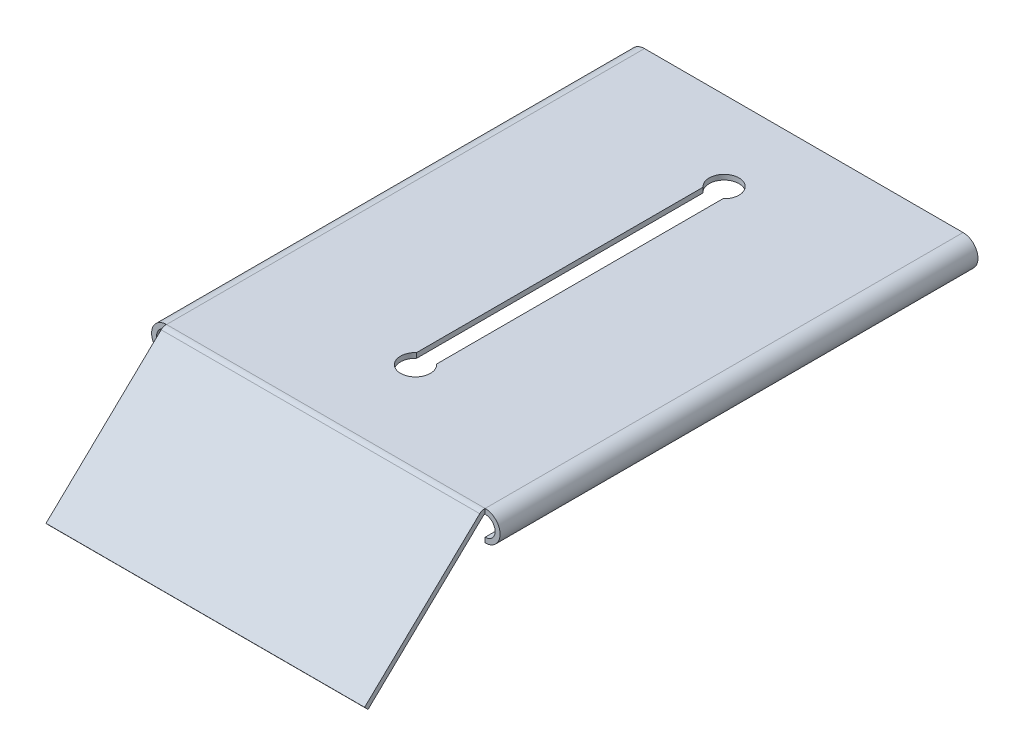
SolidWorks part; units mm, degrees
ref_plane "Front Plane" through (0, 0, 0) normal (0, 0, 1) x (1, 0, 0)
ref_plane "Top Plane" through (0, 0, 0) normal (0, 1, 0) x (1, 0, 0)
ref_plane "Right Plane" through (0, 0, 0) normal (1, 0, 0) x (0, 0, -1)
sketch "Sketch1" plane through (0, 0, 0) normal (0, 0, 1) x (1, 0, 0)
  line L0 (0, 0) -> (-101.6, 0)
  arc A0 (0, 0) -> (0, -6.35) centre (0, -3.175) cw
  arc A1 (-101.6, 0) -> (-101.6, -6.35) centre (-101.6, -3.175) ccw
  dimension "D1" = 6.35
  dimension "D2" = 101.6
extrude "Extrude-Thin1" add sketch "Sketch1" along normal blind 152.4 thin
sketch "Sketch3" plane through (0, 1.5875, 0) normal (0, 1, 0) x (1, 0, 0)
  line L0 (-50.8, 0) -> (-50.8, -152.4) construction
  line L1 (0, 0) -> (-101.6, 0) construction
  line L2 (0, -152.4) -> (-101.6, -152.4) construction
  line L3 (-53.975, -120.2752) -> (-53.975, -28.9498)
  line L4 (-50.8, -25.4) -> (-50.8, -123.825) construction
  line L6 (-47.625, -120.2752) -> (-47.625, -28.9498)
  line L7 (-53.975, -120.2752) -> (-47.625, -28.9498) construction
  line L8 (-53.975, -28.9498) -> (-47.625, -120.2752) construction
  arc A0 (-53.975, -28.9498) -> (-47.625, -28.9498) centre (-50.8, -25.4) cw
  arc A1 (-47.625, -120.2752) -> (-53.975, -120.2752) centre (-50.8, -123.825) cw
  point P7 (-50.8, -74.6125)
  dimension "D2" = 4.7625
  dimension "D3" = 123.825
  dimension "D1" = 6.35
  dimension "D4" = 25.4
extrude "Cut-Extrude1" cut sketch "Sketch3" against normal through all
sketch "Sketch4" plane through (0, 0, 0) normal (1, 0, 0) x (0, 0, -1)
  line L0 (-154.1261, 0.9974) -> (-190.8442, -34.1084)
  line L1 (-190.8442, -34.1084) -> (-189.7472, -35.2558)
  line L2 (-189.7472, -35.2558) -> (-153.029, -0.15)
  line L3 (-152.4, 0) -> (-152.4, 1.5875)
  line L4 (-154.1261, 0.9974) -> (-153.029, -0.15) construction
  arc A0 (-154.1261, 0.9974) -> (-152.4, 1.5875) centre (-152.6256, -0.5719) cw
  arc A1 (-153.029, -0.15) -> (-152.4, 0) centre (-152.5861, -0.6133) cw
  dimension "D2" = 50.8
extrude "Boss-Extrude1" add sketch "Sketch4" against normal up to vertex (101.6 mm away) up to point (-101.6, 1.5875, 152.4)
